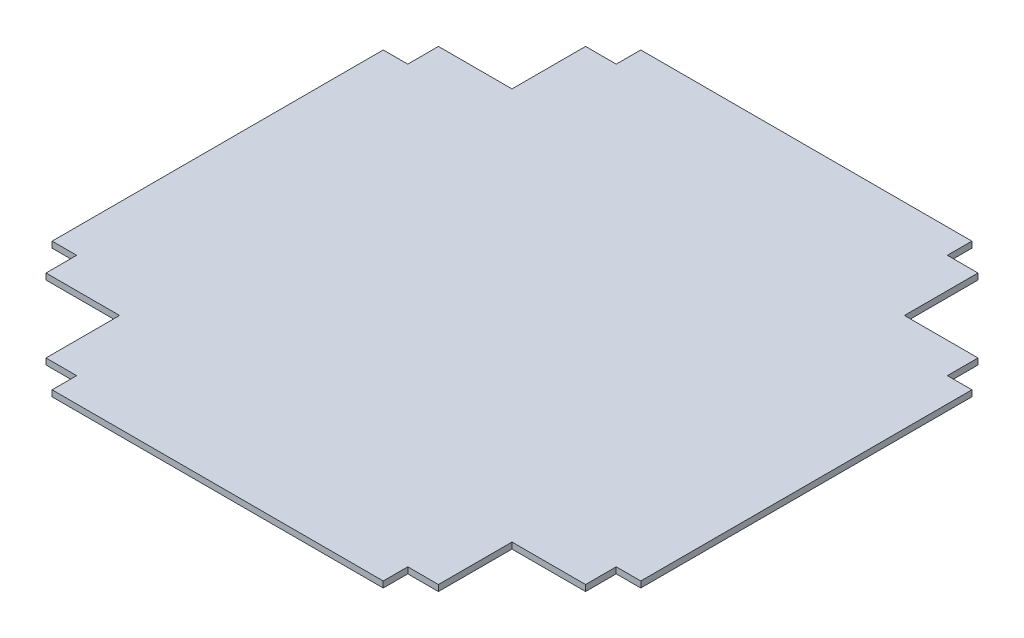
SolidWorks part; units mm, degrees
ref_plane "Front Plane" through (0, 0, 0) normal (0, 0, 1) x (1, 0, 0)
ref_plane "Top Plane" through (0, 0, 0) normal (0, 1, 0) x (1, 0, 0)
ref_plane "Right Plane" through (0, 0, 0) normal (1, 0, 0) x (0, 0, -1)
sketch "Sketch1" plane through (0, 0, 0) normal (0, 1, 0) x (1, 0, 0)
  line L1 (0, 0) -> (609.6, 0)
  line L2 (0, 0) -> (0, 609.6)
  line L3 (0, 609.6) -> (609.6, 609.6)
  line L4 (609.6, 0) -> (609.6, 609.6)
  dimension "D1" = 609.6
  dimension "D2" = 609.6
extrude "Boss-Extrude1" add sketch "Sketch1" along normal blind 6.35
sketch "Sketch2" plane through (0, 6.35, 0) normal (0, 1, 0) x (1, 0, 0)
  line L0 (609.6, 0) -> (476.25, 0)
  line L49 (0, 0) -> (609.6, 0) construction
  line L50 (476.25, 0) -> (476.25, 25.4)
  line L51 (476.25, 25.4) -> (508, 25.4)
  line L52 (508, 25.4) -> (508, 101.6)
  line L53 (508, 101.6) -> (584.2, 101.6)
  line L54 (584.2, 101.6) -> (584.2, 133.35)
  line L55 (584.2, 133.35) -> (609.6, 133.35)
  line L56 (609.6, 0) -> (609.6, 609.6) construction
  line L57 (609.6, 133.35) -> (609.6, 0)
  line L58 (304.8, 609.6) -> (304.8, 0) construction
  line L59 (609.6, 609.6) -> (0, 609.6) construction
  line L60 (0, 304.8) -> (609.6, 304.8) construction
  line L61 (0, 609.6) -> (0, 0) construction
  line L62 (0, 133.35) -> (0, 0)
  line L63 (25.4, 133.35) -> (0, 133.35)
  line L64 (25.4, 101.6) -> (25.4, 133.35)
  line L65 (101.6, 101.6) -> (25.4, 101.6)
  line L66 (101.6, 25.4) -> (101.6, 101.6)
  line L67 (133.35, 25.4) -> (101.6, 25.4)
  line L68 (133.35, 0) -> (133.35, 25.4)
  line L69 (0, 0) -> (133.35, 0)
  line L86 (0, 609.6) -> (133.35, 609.6)
  line L87 (133.35, 609.6) -> (133.35, 584.2)
  line L88 (133.35, 584.2) -> (101.6, 584.2)
  line L89 (101.6, 584.2) -> (101.6, 508)
  line L90 (101.6, 508) -> (25.4, 508)
  line L91 (25.4, 508) -> (25.4, 476.25)
  line L92 (25.4, 476.25) -> (0, 476.25)
  line L93 (0, 476.25) -> (0, 609.6)
  line L94 (609.6, 476.25) -> (609.6, 609.6)
  line L95 (584.2, 476.25) -> (609.6, 476.25)
  line L96 (584.2, 508) -> (584.2, 476.25)
  line L97 (508, 508) -> (584.2, 508)
  line L98 (508, 584.2) -> (508, 508)
  line L99 (476.25, 584.2) -> (508, 584.2)
  line L100 (476.25, 609.6) -> (476.25, 584.2)
  line L101 (609.6, 609.6) -> (476.25, 609.6)
  dimension "D1" = 101.6
  dimension "D2" = 31.75
  dimension "1" = 25.4
extrude "Cut-Extrude1" cut sketch "Sketch2" against normal through all
